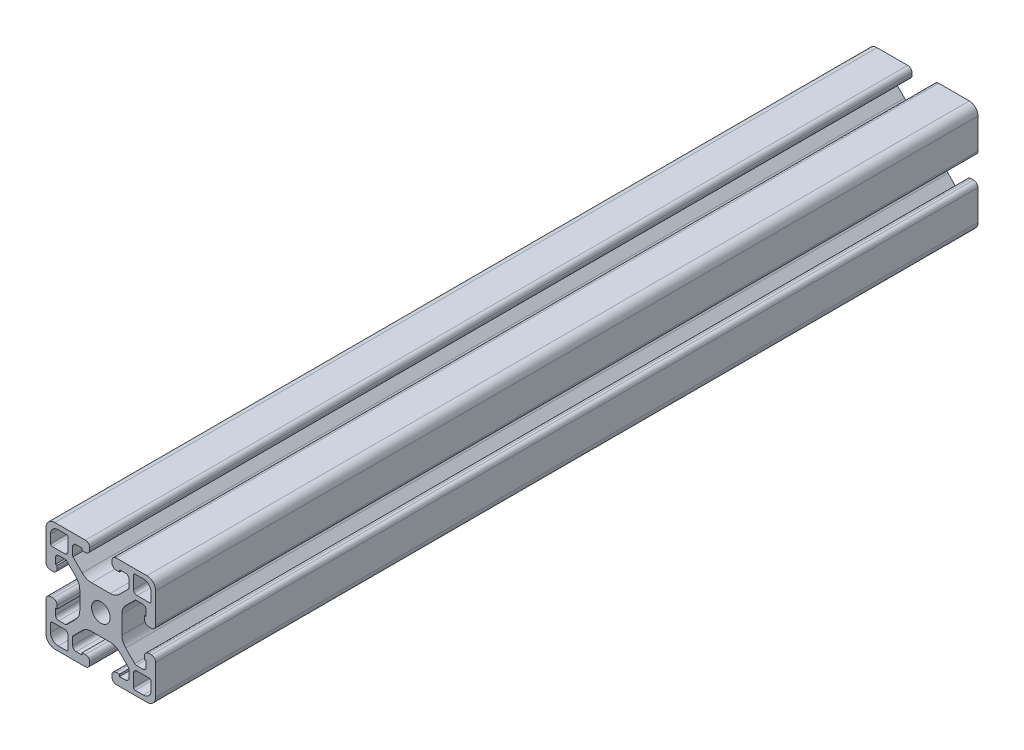
SolidWorks part; units mm, degrees
material "6105-T5 Aluminum"
ref_plane "Front Plane" through (0, 0, 0) normal (0, 0, 1) x (1, 0, 0)
ref_plane "Top Plane" through (0, 0, 0) normal (0, 1, 0) x (1, 0, 0)
ref_plane "Right Plane" through (0, 0, 0) normal (1, 0, 0) x (0, 0, -1)
sketch "Sketch1" plane through (0, 0, 0) normal (0, 0, 1) x (1, 0, 0)
  line L0 (0, 20.9056) -> (0, -8.0496) construction
  line L1 (7.685, 3.3582) -> (7.685, -3.3582)
  line L2 (12.3735, 10.0183) -> (9.0741, 6.7149)
  line L3 (15.2988, 10.2794) -> (13.0032, 10.2794)
  line L4 (16.5688, 6.9014) -> (16.5688, 9.0094)
  line L5 (15.94, 6.9014) -> (16.5688, 6.9014)
  line L6 (15.94, 5.7581) -> (15.94, 6.9014)
  line L7 (18.43, 4.1881) -> (17.51, 4.1881)
  line L8 (20, 13.1862) -> (20, 5.7581)
  line L9 (20, 16.83) -> (20, 13.1862)
  line L10 (13.0045, 20) -> (16.83, 20)
  line L11 (5.63, 20) -> (13.0045, 20)
  line L12 (4.06, 17.6962) -> (4.06, 18.43)
  line L13 (6.7839, 16.1262) -> (5.63, 16.1262)
  line L14 (6.7839, 16.8867) -> (6.7839, 16.1262)
  line L15 (9.015, 16.8867) -> (6.7839, 16.8867)
  line L16 (10.285, 12.9222) -> (10.285, 15.6167)
  line L17 (6.7706, 9.0783) -> (10.1664, 12.4784)
  line L18 (12.57, 18.35) -> (15.55, 18.35)
  line L19 (11.94, 13.21) -> (11.94, 17.72)
  line L20 (17.72, 11.94) -> (13.21, 11.94)
  line L21 (18.35, 15.55) -> (18.35, 12.57)
  line L22 (-12.3735, -10.0183) -> (-9.0741, -6.7149)
  line L23 (-15.2988, -10.2794) -> (-13.0032, -10.2794)
  line L24 (-16.5688, -6.9014) -> (-16.5688, -9.0094)
  line L25 (-15.94, -6.9014) -> (-16.5688, -6.9014)
  line L26 (-15.94, -5.7581) -> (-15.94, -6.9014)
  line L27 (-18.43, -4.1881) -> (-17.51, -4.1881)
  line L28 (-20, -13.1862) -> (-20, -5.7581)
  line L29 (-20, -16.83) -> (-20, -13.1862)
  line L30 (-13.0045, -20) -> (-16.83, -20)
  line L31 (-5.63, -20) -> (-13.0045, -20)
  line L32 (-4.06, -17.6962) -> (-4.06, -18.43)
  line L33 (-6.7839, -16.1262) -> (-5.63, -16.1262)
  line L34 (-6.7839, -16.8867) -> (-6.7839, -16.1262)
  line L35 (-9.015, -16.8867) -> (-6.7839, -16.8867)
  line L36 (-10.285, -12.9222) -> (-10.285, -15.6167)
  line L37 (-6.7706, -9.0783) -> (-10.1664, -12.4784)
  line L38 (3.4098, -7.685) -> (-3.4098, -7.685)
  line L39 (-12.57, -18.35) -> (-15.55, -18.35)
  line L40 (-11.94, -13.21) -> (-11.94, -17.72)
  line L41 (-17.72, -11.94) -> (-13.21, -11.94)
  line L42 (-18.35, -15.55) -> (-18.35, -12.57)
  line L43 (18.35, -15.55) -> (18.35, -12.57)
  line L44 (-7.685, 0) -> (7.685, 0) construction
  line L45 (-18.35, 15.55) -> (-18.35, 12.57)
  line L46 (-17.72, 11.94) -> (-13.21, 11.94)
  line L47 (-11.94, 13.21) -> (-11.94, 17.72)
  line L48 (-12.57, 18.35) -> (-15.55, 18.35)
  line L49 (17.72, -11.94) -> (13.21, -11.94)
  line L50 (11.94, -13.21) -> (11.94, -17.72)
  line L51 (12.57, -18.35) -> (15.55, -18.35)
  line L52 (6.7706, -9.0783) -> (10.1664, -12.4784)
  line L53 (10.285, -12.9222) -> (10.285, -15.6167)
  line L54 (9.015, -16.8867) -> (6.7839, -16.8867)
  line L55 (6.7839, -16.8867) -> (6.7839, -16.1262)
  line L56 (6.7839, -16.1262) -> (5.63, -16.1262)
  line L57 (4.06, -17.6962) -> (4.06, -18.43)
  line L58 (5.63, -20) -> (13.0045, -20)
  line L59 (13.0045, -20) -> (16.83, -20)
  line L60 (20, -16.83) -> (20, -13.1862)
  line L61 (20, -13.1862) -> (20, -5.7581)
  line L62 (18.43, -4.1881) -> (17.51, -4.1881)
  line L63 (15.94, -5.7581) -> (15.94, -6.9014)
  line L64 (15.94, -6.9014) -> (16.5688, -6.9014)
  line L65 (16.5688, -6.9014) -> (16.5688, -9.0094)
  line L66 (15.2988, -10.2794) -> (13.0032, -10.2794)
  line L67 (12.3735, -10.0183) -> (9.0741, -6.7149)
  line L70 (3.4098, 7.685) -> (-3.4098, 7.685)
  line L71 (-6.7706, 9.0783) -> (-10.1664, 12.4784)
  line L72 (-10.285, 12.9222) -> (-10.285, 15.6167)
  line L73 (-9.015, 16.8867) -> (-6.7839, 16.8867)
  line L74 (-6.7839, 16.8867) -> (-6.7839, 16.1262)
  line L75 (-6.7839, 16.1262) -> (-5.63, 16.1262)
  line L76 (-4.06, 17.6962) -> (-4.06, 18.43)
  line L77 (-5.63, 20) -> (-13.0045, 20)
  line L78 (-13.0045, 20) -> (-16.83, 20)
  line L79 (-20, 16.83) -> (-20, 13.1862)
  line L80 (-20, 13.1862) -> (-20, 5.7581)
  line L81 (-18.43, 4.1881) -> (-17.51, 4.1881)
  line L82 (-15.94, 5.7581) -> (-15.94, 6.9014)
  line L83 (-15.94, 6.9014) -> (-16.5688, 6.9014)
  line L84 (-16.5688, 6.9014) -> (-16.5688, 9.0094)
  line L85 (-15.2988, 10.2794) -> (-13.0032, 10.2794)
  line L86 (-12.3735, 10.0183) -> (-9.0741, 6.7149)
  line L87 (-7.685, 3.3582) -> (-7.685, -3.3582)
  arc A0 (7.685, 3.3582) -> (9.0741, 6.7149) centre (12.435, 3.3582) cw
  arc A1 (12.3735, 10.0183) -> (13.0032, 10.2794) centre (13.0032, 9.3894) cw
  arc A2 (15.2988, 10.2794) -> (16.5688, 9.0094) centre (15.2988, 9.0094) cw
  arc A3 (17.51, 4.1881) -> (15.94, 5.7581) centre (17.51, 5.7581) cw
  arc A4 (20, 5.7581) -> (18.43, 4.1881) centre (18.43, 5.7581) cw
  arc A5 (16.83, 20) -> (20, 16.83) centre (16.83, 16.83) cw
  arc A6 (4.06, 18.43) -> (5.63, 20) centre (5.63, 18.43) cw
  arc A7 (5.63, 16.1262) -> (4.06, 17.6962) centre (5.63, 17.6962) cw
  arc A8 (9.015, 16.8867) -> (10.285, 15.6167) centre (9.015, 15.6167) cw
  arc A9 (10.285, 12.9222) -> (10.1664, 12.4784) centre (9.395, 12.9222) cw
  arc A10 (6.7706, 9.0783) -> (3.4098, 7.685) centre (3.4098, 12.435) cw
  arc A11 (15.55, 18.35) -> (18.35, 15.55) centre (15.55, 15.55) cw
  arc A12 (11.94, 17.72) -> (12.57, 18.35) centre (12.57, 17.72) cw
  arc A13 (13.21, 11.94) -> (11.94, 13.21) centre (13.21, 13.21) cw
  arc A14 (18.35, 12.57) -> (17.72, 11.94) centre (17.72, 12.57) cw
  arc A15 (-7.685, -3.3582) -> (-9.0741, -6.7149) centre (-12.435, -3.3582) cw
  arc A16 (-12.3735, -10.0183) -> (-13.0032, -10.2794) centre (-13.0032, -9.3894) cw
  arc A17 (-15.2988, -10.2794) -> (-16.5688, -9.0094) centre (-15.2988, -9.0094) cw
  arc A18 (-17.51, -4.1881) -> (-15.94, -5.7581) centre (-17.51, -5.7581) cw
  arc A19 (-20, -5.7581) -> (-18.43, -4.1881) centre (-18.43, -5.7581) cw
  arc A20 (-16.83, -20) -> (-20, -16.83) centre (-16.83, -16.83) cw
  arc A21 (-4.06, -18.43) -> (-5.63, -20) centre (-5.63, -18.43) cw
  arc A22 (-5.63, -16.1262) -> (-4.06, -17.6962) centre (-5.63, -17.6962) cw
  arc A23 (-9.015, -16.8867) -> (-10.285, -15.6167) centre (-9.015, -15.6167) cw
  arc A24 (-10.285, -12.9222) -> (-10.1664, -12.4784) centre (-9.395, -12.9222) cw
  arc A25 (-6.7706, -9.0783) -> (-3.4098, -7.685) centre (-3.4098, -12.435) cw
  arc A26 (-15.55, -18.35) -> (-18.35, -15.55) centre (-15.55, -15.55) cw
  arc A27 (-11.94, -17.72) -> (-12.57, -18.35) centre (-12.57, -17.72) cw
  arc A28 (-13.21, -11.94) -> (-11.94, -13.21) centre (-13.21, -13.21) cw
  arc A29 (-18.35, -12.57) -> (-17.72, -11.94) centre (-17.72, -12.57) cw
  arc A30 (18.35, -12.57) -> (17.72, -11.94) centre (17.72, -12.57) ccw
  arc A31 (-18.35, 12.57) -> (-17.72, 11.94) centre (-17.72, 12.57) ccw
  arc A32 (-13.21, 11.94) -> (-11.94, 13.21) centre (-13.21, 13.21) ccw
  arc A33 (-11.94, 17.72) -> (-12.57, 18.35) centre (-12.57, 17.72) ccw
  arc A34 (-15.55, 18.35) -> (-18.35, 15.55) centre (-15.55, 15.55) ccw
  arc A35 (13.21, -11.94) -> (11.94, -13.21) centre (13.21, -13.21) ccw
  arc A36 (11.94, -17.72) -> (12.57, -18.35) centre (12.57, -17.72) ccw
  arc A37 (15.55, -18.35) -> (18.35, -15.55) centre (15.55, -15.55) ccw
  arc A38 (6.7706, -9.0783) -> (3.4098, -7.685) centre (3.4098, -12.435) ccw
  circle A39 centre (0, 0) radius 3.4
  arc A40 (10.285, -12.9222) -> (10.1664, -12.4784) centre (9.395, -12.9222) ccw
  arc A41 (9.015, -16.8867) -> (10.285, -15.6167) centre (9.015, -15.6167) ccw
  arc A42 (5.63, -16.1262) -> (4.06, -17.6962) centre (5.63, -17.6962) ccw
  arc A43 (4.06, -18.43) -> (5.63, -20) centre (5.63, -18.43) ccw
  arc A44 (16.83, -20) -> (20, -16.83) centre (16.83, -16.83) ccw
  arc A45 (20, -5.7581) -> (18.43, -4.1881) centre (18.43, -5.7581) ccw
  arc A46 (17.51, -4.1881) -> (15.94, -5.7581) centre (17.51, -5.7581) ccw
  arc A47 (15.2988, -10.2794) -> (16.5688, -9.0094) centre (15.2988, -9.0094) ccw
  arc A48 (12.3735, -10.0183) -> (13.0032, -10.2794) centre (13.0032, -9.3894) ccw
  arc A49 (7.685, -3.3582) -> (9.0741, -6.7149) centre (12.435, -3.3582) ccw
  arc A51 (-6.7706, 9.0783) -> (-3.4098, 7.685) centre (-3.4098, 12.435) ccw
  arc A52 (-10.285, 12.9222) -> (-10.1664, 12.4784) centre (-9.395, 12.9222) ccw
  arc A53 (-9.015, 16.8867) -> (-10.285, 15.6167) centre (-9.015, 15.6167) ccw
  arc A54 (-5.63, 16.1262) -> (-4.06, 17.6962) centre (-5.63, 17.6962) ccw
  arc A55 (-4.06, 18.43) -> (-5.63, 20) centre (-5.63, 18.43) ccw
  arc A56 (-16.83, 20) -> (-20, 16.83) centre (-16.83, 16.83) ccw
  arc A57 (-20, 5.7581) -> (-18.43, 4.1881) centre (-18.43, 5.7581) ccw
  arc A58 (-17.51, 4.1881) -> (-15.94, 5.7581) centre (-17.51, 5.7581) ccw
  arc A59 (-15.2988, 10.2794) -> (-16.5688, 9.0094) centre (-15.2988, 9.0094) ccw
  arc A60 (-12.3735, 10.0183) -> (-13.0032, 10.2794) centre (-13.0032, 9.3894) ccw
  arc A61 (-7.685, 3.3582) -> (-9.0741, 6.7149) centre (-12.435, 3.3582) ccw
  point P5 (0, 7.685)
  point P200 (0, -7.685)
  dimension "D7" = 6.8
  dimension "D1" = 40
  dimension "D2" = 20.57
  dimension "D3" = 12.315
  dimension "D4" = 15.37
  dimension "D5" = 8.12
  dimension "D6" = 20
  dimension "D8" = 3.3
  dimension "D9" = 4.06
extrude "Extrude1" add sketch "Sketch1" against normal blind 300
